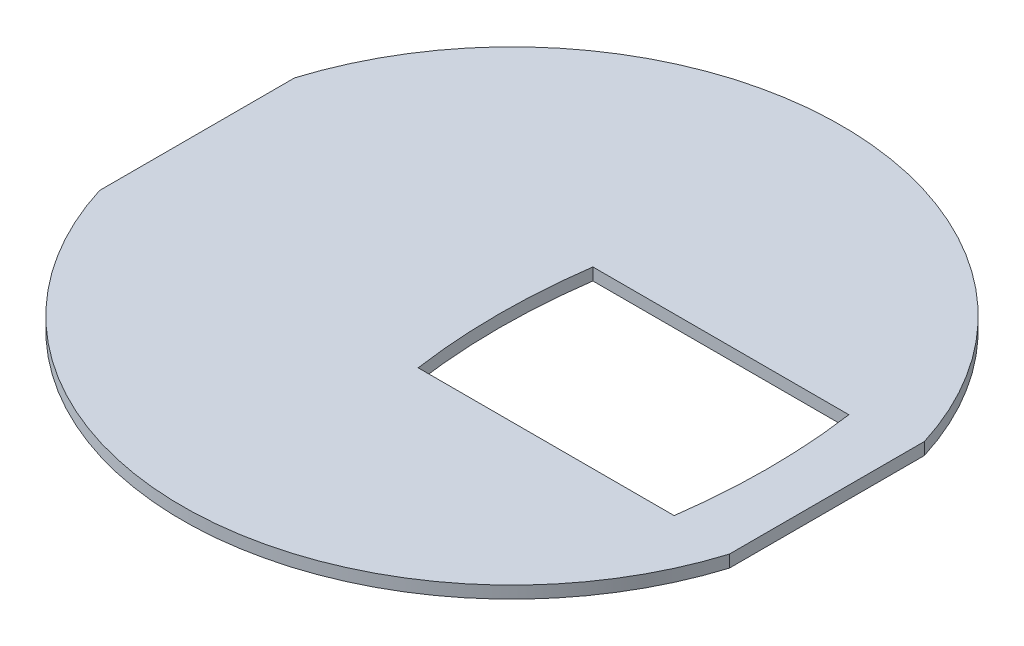
SolidWorks part; units mm, degrees
ref_plane "Front" through (0, 0, 0) normal (0, 0, 1) x (1, 0, 0)
ref_plane "Top" through (0, 0, 0) normal (0, 1, 0) x (1, 0, 0)
ref_plane "Right" through (0, 0, 0) normal (1, 0, 0) x (0, 0, -1)
sketch "Çizim1" plane through (0, 0, 0) normal (0, 1, 0) x (1, 0, 0)
  line L0 (-77.5, 24) -> (-77.5, -24)
  line L1 (77.5, 24) -> (77.5, -24)
  arc A0 (-77.5, -24) -> (77.5, -24) centre (0, 0) ccw
  arc A1 (77.5, 24) -> (-77.5, 24) centre (0, 0) ccw
  dimension "D1" = 48
  dimension "D3" = 155
  dimension "D2" = 48
extrude "Yükseklik-Ekstrüzyon1" add sketch "Çizim1" along normal blind 3
sketch "Çizim4" plane through (0, 3, 0) normal (0, 1, 0) x (1, 0, 0)
  line L0 (77.5, -24) -> (77.5, 24) construction
  line L1 (62.5, 20.4049) -> (-0.5, 20.4049)
  line L3 (62.5, -22.5951) -> (-0.5, -22.5951)
  arc A0 (-0.5, 20.4049) -> (-0.5, -22.5951) centre (150.3713, -1.0951) ccw
  arc A1 (62.5, 20.4049) -> (62.5, -22.5951) centre (-89.0647, -1.0951) cw
  point P8 (50, 21.0742)
  point P9 (60, 20.5537)
  point P10 (62.5, 20.4049)
  dimension "D4" = 15
  dimension "D1" = 63
  dimension "D2" = 43
  dimension "D3" = 63
extrude "Kes-Ekstrüzyon2" cut sketch "Çizim4" against normal blind 5.5
